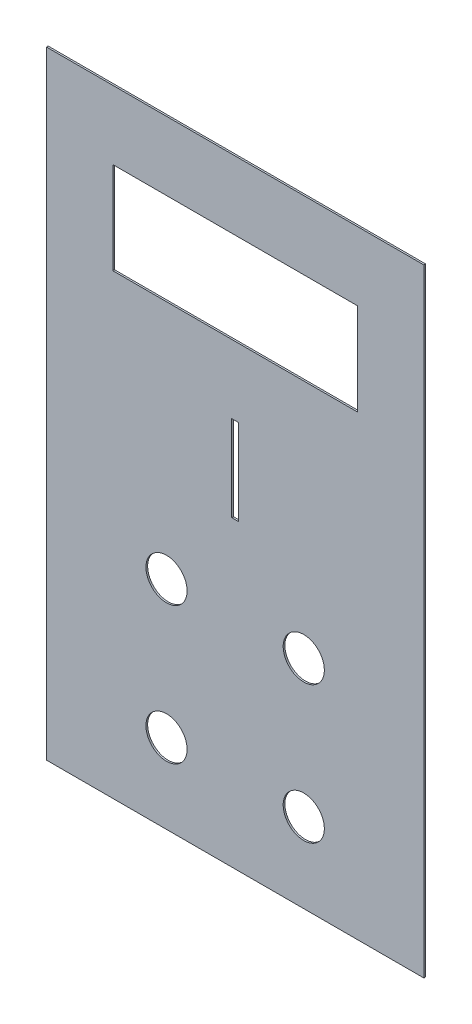
SolidWorks part; units mm, degrees
ref_plane "Front Plane" through (0, 0, 0) normal (0, 0, 1) x (1, 0, 0)
ref_plane "Top Plane" through (0, 0, 0) normal (0, 1, 0) x (1, 0, 0)
ref_plane "Right Plane" through (0, 0, 0) normal (1, 0, 0) x (0, 0, -1)
sketch "Sketch1" plane through (0, 0, 0) normal (0, 0, 1) x (1, 0, 0)
  line L1 (-55, -90) -> (55, -90)
  line L2 (-55, -90) -> (-55, 90)
  line L3 (-55, 90) -> (55, 90)
  line L4 (55, -90) -> (55, 90)
  line L5 (-55, -90) -> (55, 90) construction
  line L6 (-55, 90) -> (55, -90) construction
  point P0 (0, 0)
  dimension "D1" = 110
  dimension "D2" = 180
extrude "Boss-Extrude1" add sketch "Sketch1" along normal blind 0.5
sketch "Sketch2" plane through (0, 0, 0.5) normal (0, 0, 1) x (1, 0, 0)
  line L1 (-35.65, 43.2) -> (35.65, 43.2)
  line L2 (-35.65, 43.2) -> (-35.65, 70)
  line L3 (-35.65, 70) -> (35.65, 70)
  line L4 (35.65, 43.2) -> (35.65, 70)
  line L5 (-35.65, 43.2) -> (35.65, 70) construction
  line L6 (-35.65, 70) -> (35.65, 43.2) construction
  line L7 (-1, -1.8) -> (1, -1.8)
  line L8 (-1, -1.8) -> (-1, 23.2)
  line L9 (-1, 23.2) -> (1, 23.2)
  line L10 (1, -1.8) -> (1, 23.2)
  line L11 (-1, -1.8) -> (1, 23.2) construction
  line L12 (-1, 23.2) -> (1, -1.8) construction
  line L13 (55, 90) -> (-55, 90) construction
  circle A0 centre (-20, -26.8) radius 6
  circle A1 centre (20, -26.8) radius 6
  circle A2 centre (20, -66.8) radius 6
  circle A3 centre (-20, -66.8) radius 6
  point P0 (0, 56.6)
  point P5 (0, 10.7)
  dimension "D1" = 71.3
  dimension "D7" = 12
  dimension "D8" = 12
  dimension "D9" = 12
  dimension "D10" = 12
  dimension "D2" = 26.8
  dimension "D3" = 20
  dimension "D4" = 2
  dimension "D5" = 25
  dimension "D6" = 20
  dimension "D11" = 40
  dimension "D12" = 20
  dimension "D13" = 40
  dimension "D14" = 25
extrude "Cut-Extrude1" cut sketch "Sketch2" against normal through all
